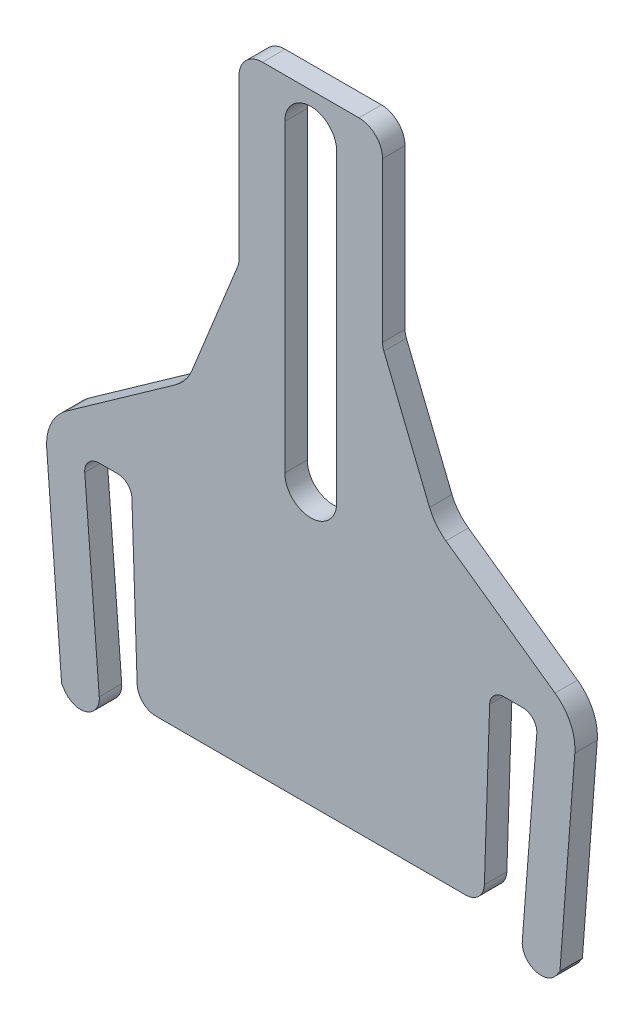
SolidWorks part; units mm, degrees
material "AISI 1010 Barra de acero laminada en caliente"
ref_plane "Alzado" through (0, 0, 0) normal (0, 0, 1) x (1, 0, 0)
ref_plane "Planta" through (0, 0, 0) normal (0, 1, 0) x (1, 0, 0)
ref_plane "Vista lateral" through (0, 0, 0) normal (1, 0, 0) x (0, 0, -1)
sketch "Croquis1" plane through (0, 0, 0) normal (0, 0, 1) x (1, 0, 0)
  line L0 (25.1194, 158.385) -> (19.4107, 65.0351)
  line L2 (-25.1194, 158.385) -> (-19.4107, 65.0351)
  line L4 (20.4721, 115.1572) -> (17.4144, 65.1572)
  line L5 (-21.1464, 126.1826) -> (-17.4144, 65.1572)
  line L6 (23.1231, 158.5071) -> (17.4144, 65.1572) construction
  line L7 (-23.1231, 158.5071) -> (-17.4144, 65.1572) construction
  line L8 (20.4721, 115.1572) -> (-21.1464, 126.1826)
  line L9 (17.4144, 65.1572) -> (-17.4144, 65.1572)
  line L10 (0, 76.6637) -> (0, 0) construction
  line L13 (52.7841, -29.7437) -> (43.643, -43.2466)
  line L14 (43.643, -43.2466) -> (48.1336, 14.6904)
  line L15 (48.1336, 14.6904) -> (37.9924, 14.6904)
  line L16 (37.9924, 14.6904) -> (36.6528, -25.7332)
  line L17 (15.2082, 65.1572) -> (56.9967, 25.832)
  line L18 (56.9967, 25.832) -> (52.7841, -29.7437)
  line L19 (36.6528, -25.7332) -> (-36.6528, -25.7332)
  line L20 (0, 0) -> (0, -56.0179) construction
  line L21 (-15.2082, 65.1572) -> (-15.2082, 103.7062)
  line L22 (-15.2082, 65.1572) -> (-56.9967, 25.832)
  line L23 (-56.9967, 25.832) -> (-52.7841, -29.7437)
  line L24 (-37.9924, 14.6904) -> (-36.6528, -25.7332)
  line L25 (-48.1336, 14.6904) -> (-37.9924, 14.6904)
  line L26 (-43.643, -43.2466) -> (-48.1336, 14.6904)
  line L27 (-52.7841, -29.7437) -> (-43.643, -43.2466)
  line L28 (-15.2082, 103.7062) -> (15.2082, 103.7062)
  line L29 (15.2082, 103.7062) -> (15.2082, 65.1572)
  line L30 (0, 82.5569) -> (0, 42.5569) construction
  line L31 (5.5, 82.5569) -> (5.5, 42.5569)
  line L32 (-5.5, 82.5569) -> (-5.5, 42.5569)
  arc A3 (5.5, 82.5569) -> (-5.5, 82.5569) centre (0, 82.5569) ccw
  arc A4 (-5.5, 42.5569) -> (5.5, 42.5569) centre (0, 42.5569) ccw
  point P12 (0, 62.5569)
  point P29 (0, -25.7332)
  dimension "D4" = 5.5
  dimension "D5" = 40
  dimension "D3" = 50
  dimension "D1" = 2
  dimension "D2" = 2
extrude "Saliente-Extruir1" add sketch "Croquis1" along normal mid plane 4.76 contours A3 L31 L9 L29 L28 L21 L32 | A4 L32 L9 L22 L23 L27 L26 L25 L24 L19 L16 L15 L14 L13 L18 L17 L31
fillet "Redondeo1" radius 4 2 edges at (43.643, -43.2466, 0) (-43.643, -43.2466, 0)
fillet "Redondeo2" radius 4 2 edges at (36.6528, -25.7332, 0) (-36.6528, -25.7332, 0)
fillet "Redondeo3" radius 4 6 edges at (15.2082, 65.1572, 0) (-15.2082, 65.1572, 0) (-15.2082, 103.7062, 0) (15.2082, 103.7062, 0) (56.9967, 25.832, 0) (-56.9967, 25.832, 0)
fillet "Redondeo4" radius 3 4 edges at (-37.9924, 14.6904, 0) (-48.1336, 14.6904, 0) (37.9924, 14.6904, 0) (48.1336, 14.6904, 0)
sketch "Croquis2" plane through (0, 0, -2.38) normal (0, 0, -1) x (-1, 0, 0)
  line L0 (0, 82.5569) -> (0, 12.5569) construction
  line L1 (5.5, 82.5569) -> (5.5, 12.5569)
  line L2 (-5.5, 82.5569) -> (-5.5, 12.5569)
  arc A0 (5.5, 82.5569) -> (-5.5, 82.5569) centre (0, 82.5569) ccw
  arc A1 (-5.5, 12.5569) -> (5.5, 12.5569) centre (0, 12.5569) ccw
  arc A2 (5.5, 82.5569) -> (-5.5, 82.5569) centre (0, 82.5569) ccw construction
  point P4 (0, 47.5569)
  dimension "D1" = 70
extrude "Cortar-Extruir1" cut sketch "Croquis2" against normal through all both and the other way through all
sketch "Croquis3" plane through (0, 0, 2.38) normal (0, 0, 1) x (1, 0, 0)
  line L0 (-56.366, 17.5117) -> (-28.642, 37.148)
  line L1 (-15.2082, 66.8856) -> (-15.2082, 82.5569)
  line L2 (0, 67.0706) -> (0, 20.8437) construction
  line L3 (-56.8523, 23.9264) -> (-52.7841, -29.7437) construction
  line L4 (-25.1533, 41.5541) -> (-15.5008, 65.3839)
  line L5 (56.366, 17.5117) -> (28.642, 37.148)
  line L6 (25.1533, 41.5541) -> (15.5008, 65.3839)
  line L7 (-15.2082, 66.8856) -> (-15.2082, 99.7062) construction
  line L8 (-15.2082, 82.5569) -> (15.2082, 82.5569)
  line L9 (15.2082, 99.7062) -> (15.2082, 66.8856) construction
  line L10 (15.2082, 82.5569) -> (15.2082, 66.8856)
  line L11 (56.366, 17.5117) -> (71.4671, 17.5117)
  line L12 (71.4671, 17.5117) -> (71.4671, 120.0549)
  line L13 (71.4671, 120.0549) -> (-63.8513, 120.0549)
  line L14 (-63.8513, 120.0549) -> (-63.8513, 17.5117)
  line L15 (-63.8513, 17.5117) -> (-56.366, 17.5117)
  arc A0 (-15.5008, 65.3839) -> (-15.2082, 66.8856) centre (-19.2082, 66.8856) ccw
  arc A1 (-16.4669, 63.9726) -> (-15.2082, 66.8856) centre (-19.2082, 66.8856) ccw construction
  arc A2 (-28.642, 37.148) -> (-25.1533, 41.5541) centre (-34.4218, 45.3084) ccw
  arc A3 (28.642, 37.148) -> (25.1533, 41.5541) centre (34.4218, 45.3084) cw
  arc A4 (15.2082, 66.8856) -> (16.4669, 63.9726) centre (19.2082, 66.8856) ccw construction
  arc A5 (15.2082, 66.8856) -> (15.5008, 65.3839) centre (19.2082, 66.8856) ccw
  dimension "D1" = 10
extrude "Cortar-Extruir2" cut sketch "Croquis3" against normal through all
sketch "Croquis4" plane through (0, 0, 2.38) normal (0, 0, 1) x (1, 0, 0)
  line L0 (-5.5, 32.5569) -> (-5.5, 0)
  line L1 (-5.5, 0) -> (5.5, 0)
  line L2 (5.5, 0) -> (5.5, 32.5569)
  line L4 (5.5, 82.5569) -> (5.5, 12.5569) construction
  line L8 (5.5, 97.0569) -> (5.5, 82.5569)
  line L9 (-5.5, 97.0569) -> (-5.5, 82.5569)
  line L10 (15.2082, 82.5569) -> (15.2082, 100.5569)
  line L11 (10.2082, 105.5569) -> (-10.2082, 105.5569)
  line L12 (-15.2082, 100.5569) -> (-15.2082, 82.5569)
  line L13 (15.2082, 82.5569) -> (5.5, 82.5569)
  line L14 (-5.5, 82.5569) -> (-15.2082, 82.5569)
  arc A0 (5.5, 97.0569) -> (-5.5, 97.0569) centre (0, 97.0569) ccw
  arc A1 (-10.2082, 105.5569) -> (-15.2082, 100.5569) centre (-10.2082, 100.5569) ccw
  arc A2 (15.2082, 100.5569) -> (10.2082, 105.5569) centre (10.2082, 100.5569) ccw
  arc A3 (-5.5, 32.5569) -> (5.5, 32.5569) centre (0, 32.5569) ccw
  arc A5 (-5.5, 12.5569) -> (5.5, 12.5569) centre (0, 12.5569) ccw construction
  dimension "D1" = 11
  dimension "D3" = 3
  dimension "D4" = 5
  dimension "D5" = 5
  dimension "D6" = 20
  dimension "D7" = 11
  dimension "D2" = 20
extrude "Saliente-Extruir2" add sketch "Croquis4" against normal up to surface (4.76 mm away)
fillet "Redondeo5" radius 10 2 edges at (56.366, 17.5117, 0) (-56.366, 17.5117, 0)
